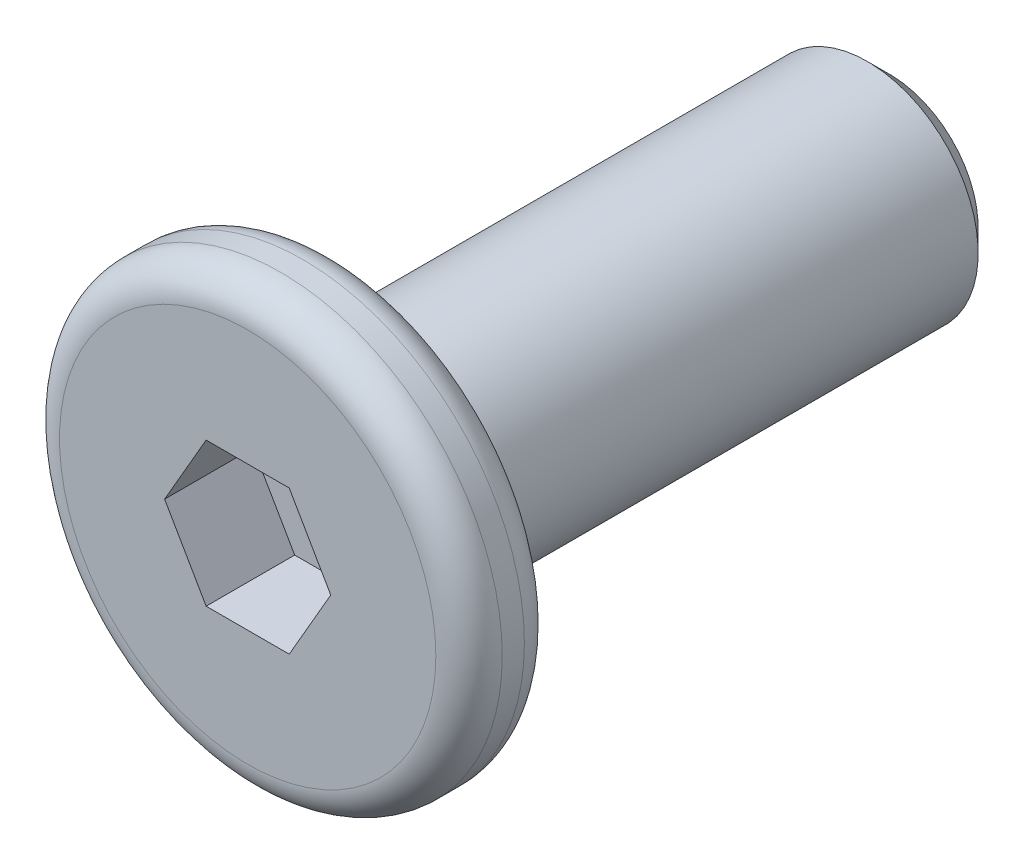
SolidWorks part; units mm, degrees
ref_plane "前视基准面" through (0, 0, 0) normal (0, 0, 1) x (1, 0, 0)
ref_plane "上视基准面" through (0, 0, 0) normal (0, 1, 0) x (1, 0, 0)
ref_plane "右视基准面" through (0, 0, 0) normal (1, 0, 0) x (0, 0, -1)
sketch "草图1" plane through (0, 0, 0) normal (0, 0, 1) x (1, 0, 0)
  circle A0 centre (0, 0) radius 2
  dimension "D1" = 4
extrude "凸台-拉伸1" add sketch "草图1" along normal mid plane 0.8
sketch "草图2" plane through (0, 0, -0.4) normal (0, 0, -1) x (-1, 0, 0)
  circle A0 centre (0, 0) radius 1
  dimension "D1" = 2
extrude "凸台-拉伸2" add sketch "草图2" along normal blind 5
chamfer "倒角1" distance 0.2 angle 45 1 edges at (-1, 0, -5.4)
sketch "草图3" plane through (0, 0, 0.4) normal (0, 0, 1) x (1, 0, 0)
  line L1 (0.7506, 0) -> (0.3753, 0.65)
  line L2 (0.3753, 0.65) -> (-0.3753, 0.65)
  line L3 (-0.3753, 0.65) -> (-0.7506, 0)
  line L4 (-0.7506, 0) -> (-0.3753, -0.65)
  line L5 (-0.3753, -0.65) -> (0.3753, -0.65)
  line L6 (0.3753, -0.65) -> (0.7506, 0)
  circle A0 centre (0, 0) radius 0.65 construction
  dimension "D1" = 1.3
extrude "切除-拉伸1" cut sketch "草图3" against normal blind 0.8
fillet "圆角2" radius 0.3 2 edges at (2, 0, -0.4) (2, 0, 0.4)
